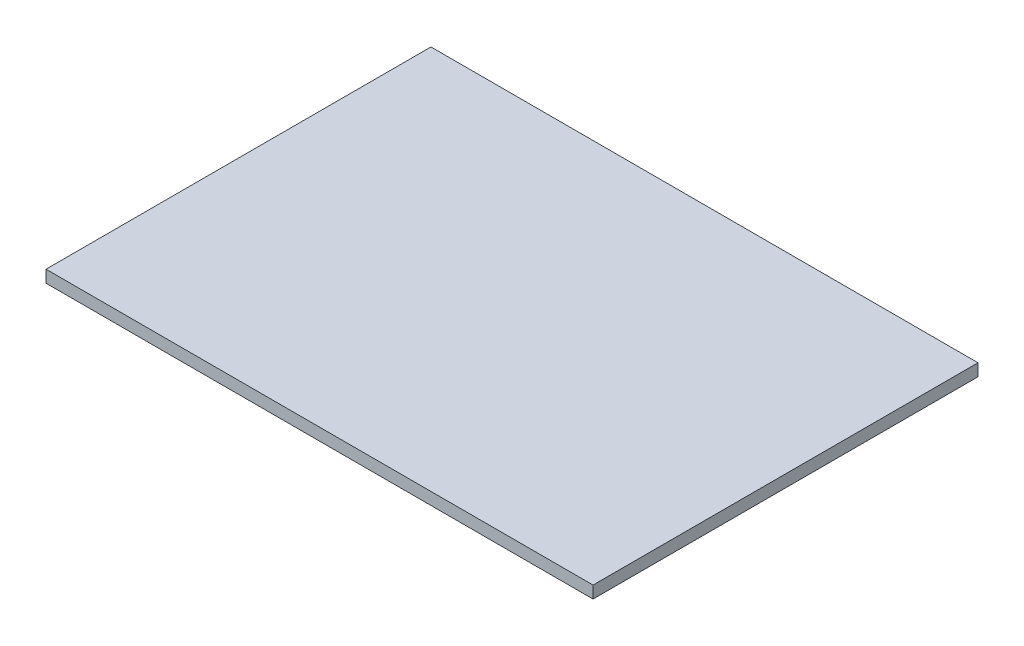
SolidWorks part; units mm, degrees
ref_plane "Front Plane" through (0, 0, 0) normal (0, 0, 1) x (1, 0, 0)
ref_plane "Top Plane" through (0, 0, 0) normal (0, 1, 0) x (1, 0, 0)
ref_plane "Right Plane" through (0, 0, 0) normal (1, 0, 0) x (0, 0, -1)
sketch "Sketch1" plane through (0, 0, 0) normal (0, 1, 0) x (1, 0, 0)
  line L1 (67.5, -47.5) -> (-67.5, -47.5)
  line L2 (67.5, -47.5) -> (67.5, 47.5)
  line L3 (67.5, 47.5) -> (-67.5, 47.5)
  line L4 (-67.5, -47.5) -> (-67.5, 47.5)
  line L5 (67.5, -47.5) -> (-67.5, 47.5) construction
  line L6 (67.5, 47.5) -> (-67.5, -47.5) construction
  point P0 (0, 0)
  dimension "D1" = 95
  dimension "D2" = 135
extrude "Boss-Extrude1" add sketch "Sketch1" along normal blind 3
